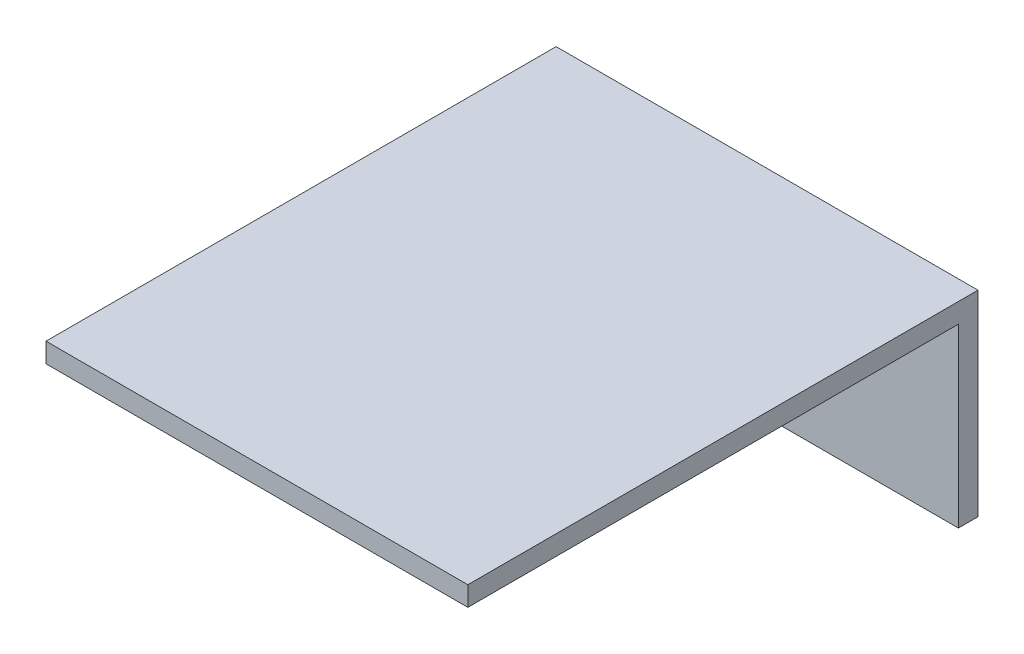
SolidWorks part; units mm, degrees
ref_plane "Plan de face" through (0, 0, 0) normal (0, 0, 1) x (1, 0, 0)
ref_plane "Plan de dessus" through (0, 0, 0) normal (0, 1, 0) x (1, 0, 0)
ref_plane "Plan de droite" through (0, 0, 0) normal (1, 0, 0) x (0, 0, -1)
sketch "Esquisse1" plane through (0, 0, 0) normal (0, 0, 1) x (1, 0, 0)
  line L1 (-21.5, -10) -> (21.5, -10)
  line L2 (-21.5, -10) -> (-21.5, 10)
  line L3 (-21.5, 10) -> (21.5, 10)
  line L4 (21.5, -10) -> (21.5, 10)
  line L5 (-21.5, -10) -> (21.5, 10) construction
  line L6 (-21.5, 10) -> (21.5, -10) construction
  point P0 (0, 0)
  dimension "D1" = 20
  dimension "D2" = 43
extrude "Boss.-Extru.1" add sketch "Esquisse1" along normal blind 52
sketch "Esquisse2" plane through (0, 0, 52) normal (0, 0, 1) x (1, 0, 0)
  line L12 (19.5, -8) -> (19.5, 8)
  line L13 (19.5, 8) -> (-19.5, 8)
  line L14 (-19.5, 8) -> (-19.5, -8)
  line L15 (-19.5, -8) -> (19.5, -8)
  line L16 (30.2089, -13.9443) -> (30.2089, 8)
  line L17 (30.2089, 8) -> (-27.0688, 8)
  line L18 (-27.0688, 8) -> (-27.0688, -13.9443)
  line L19 (-27.0688, -13.9443) -> (30.2089, -13.9443)
  dimension "D1" = 2
extrude "Enlèv. mat.-Extru.1" cut sketch "Esquisse2" against normal blind 50
